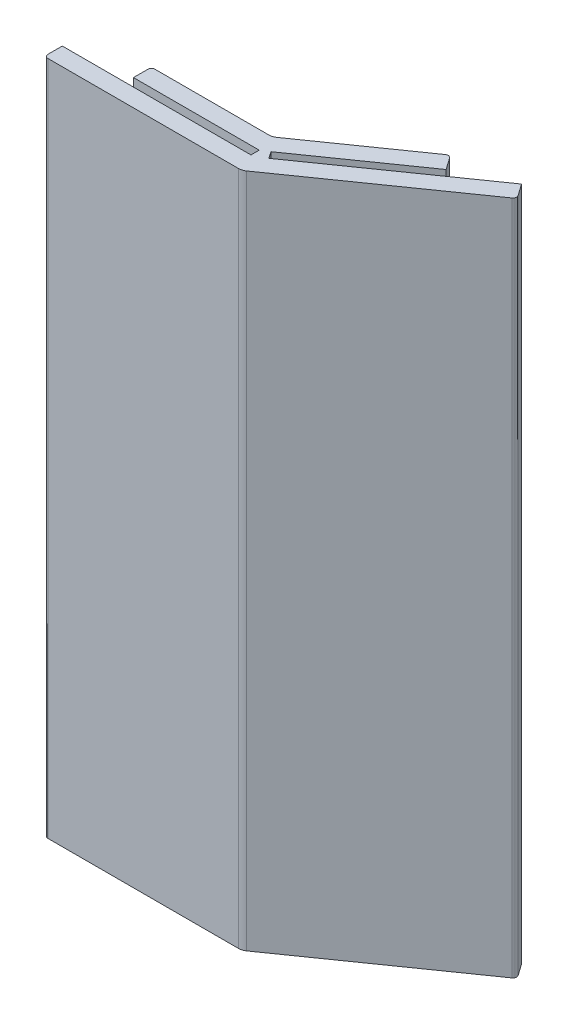
SolidWorks part; units mm, degrees
ref_plane "Front Plane" through (0, 0, 0) normal (0, 0, 1) x (1, 0, 0)
ref_plane "Top Plane" through (0, 0, 0) normal (0, 1, 0) x (1, 0, 0)
ref_plane "Right Plane" through (0, 0, 0) normal (1, 0, 0) x (0, 0, -1)
sketch "Sketch2" plane through (0, 0, 0) normal (0, 1, 0) x (1, 0, 0)
  line L0 (-0.9459, 0) -> (-54, 0)
  line L1 (-55, 1) -> (-55, 5)
  line L2 (-55, 5) -> (-2.4876, 5)
  line L3 (-2.4876, 5) -> (-2.4876, 7.3)
  line L4 (-2.4876, 7.3) -> (-37.4876, 7.3)
  line L5 (-37.4876, 7.3) -> (-37.4876, 11.3)
  line L6 (-36.4876, 12.3) -> (-4.8241, 12.3)
  line L7 (-3.1033, 12.8425) -> (24.4896, 32.1633)
  line L8 (25.8823, 31.9178) -> (28.1766, 28.6411)
  line L9 (28.1766, 28.6411) -> (-0.4937, 8.566)
  line L10 (-0.4937, 8.566) -> (0.8255, 6.6819)
  line L11 (0.8255, 6.6819) -> (42.1855, 35.6425)
  line L12 (42.1855, 35.6425) -> (44.4798, 32.3659)
  line L13 (0.7748, 0.5425) -> (44.2342, 30.9731)
  arc A0 (-55, 1) -> (-54, 0) centre (-54, 1) ccw
  arc A1 (44.2342, 30.9731) -> (44.4798, 32.3659) centre (43.6606, 31.7923) ccw
  arc A2 (25.8823, 31.9178) -> (24.4896, 32.1633) centre (25.0632, 31.3442) ccw
  arc A3 (-37.4876, 11.3) -> (-36.4876, 12.3) centre (-36.4876, 11.3) cw
  arc A4 (0.7748, 0.5425) -> (-0.9459, 0) centre (-0.9459, 3) cw
  arc A5 (-4.8241, 12.3) -> (-3.1033, 12.8425) centre (-4.8241, 15.3) ccw
  point P29 (-55, 0)
  point P32 (45.0534, 31.5467)
  point P35 (25.3087, 32.7369)
  point P38 (-37.4876, 12.3)
  point P41 (0, 0)
  dimension "D13" = 1
  dimension "D14" = 1
  dimension "D15" = 1
  dimension "D16" = 1
  dimension "D17" = 3
  dimension "D18" = 3
  dimension "D2" = 55
  dimension "D3" = 55
  dimension "D4" = 2.3
  dimension "D5" = 5
  dimension "D6" = 5
  dimension "D7" = 35
  dimension "D8" = 35
  dimension "D9" = 5
  dimension "D10" = 2.3
  dimension "D11" = 5
  dimension "D12" = 145
extrude "Boss-Extrude1" add sketch "Sketch2" along normal blind 188
